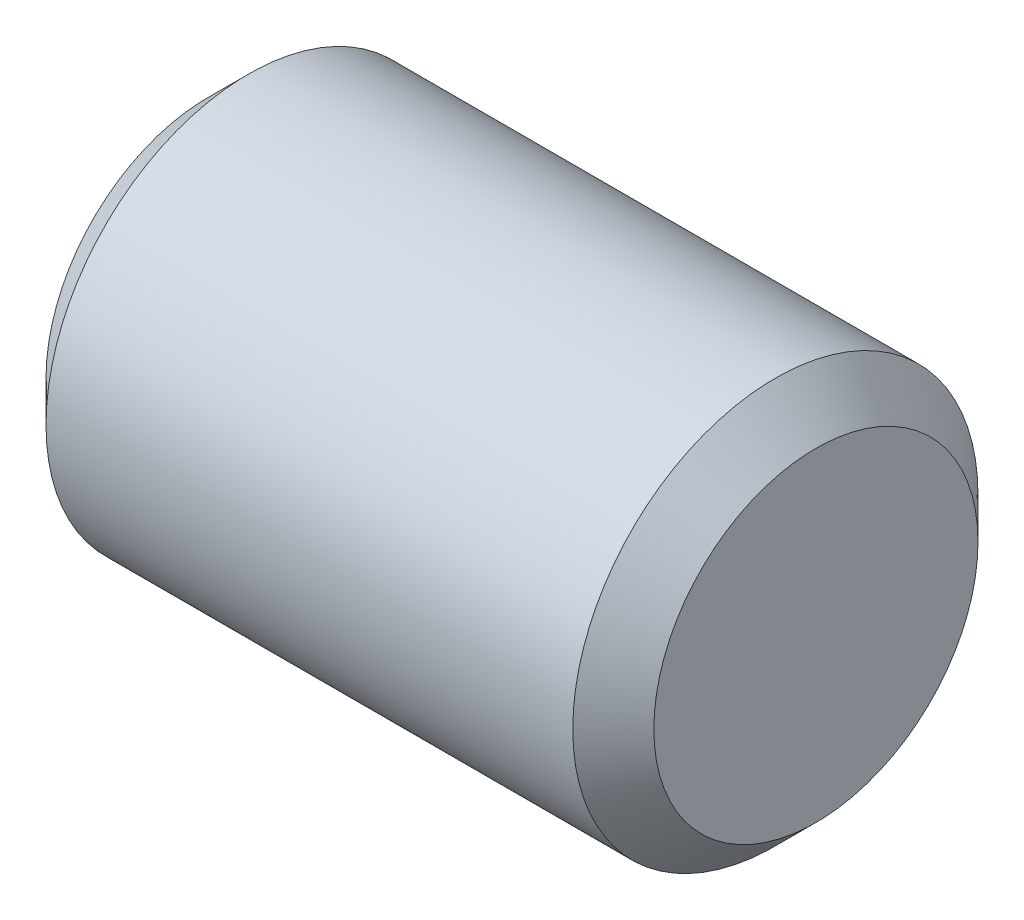
SolidWorks part; units mm, degrees
ref_plane "Front" through (0, 0, 0) normal (0, 0, 1) x (1, 0, 0)
ref_plane "Top" through (0, 0, 0) normal (0, 1, 0) x (1, 0, 0)
ref_plane "Right" through (0, 0, 0) normal (1, 0, 0) x (0, 0, -1)
sketch "Sketch1" plane through (0, 0, 0) normal (0, 0, 1) x (1, 0, 0)
  line L0 (-4.7625, 0) -> (4.7625, 0) construction
  line L1 (4.7625, 3.175) -> (4.7625, -3.175) construction
  line L2 (-4.7625, 3.175) -> (-4.7625, -3.175) construction
  dimension "Length" = 9.525
  dimension "Diameter" = 6.35
sketch "Sketch2" plane through (0, 0, 0) normal (1, 0, 0) x (0, 0, -1)
  circle A0 centre (0, 0) radius 3.175
extrude "Extrude1" add sketch "Sketch2" against normal up to vertex (4.7625 mm away) and the other way up to vertex (4.7625 mm away) up to point (-4.7625, 3.175, 0) other way up to point (4.7625, 3.175, 0)
chamfer "Chamfer1" distance 0.635 angle 45 2 edges at (4.7625, 0, -3.175) (-4.7625, 0, -3.175)
equation "\"D1@Chamfer1\" = \"Diameter@Sketch1\"*.1"
